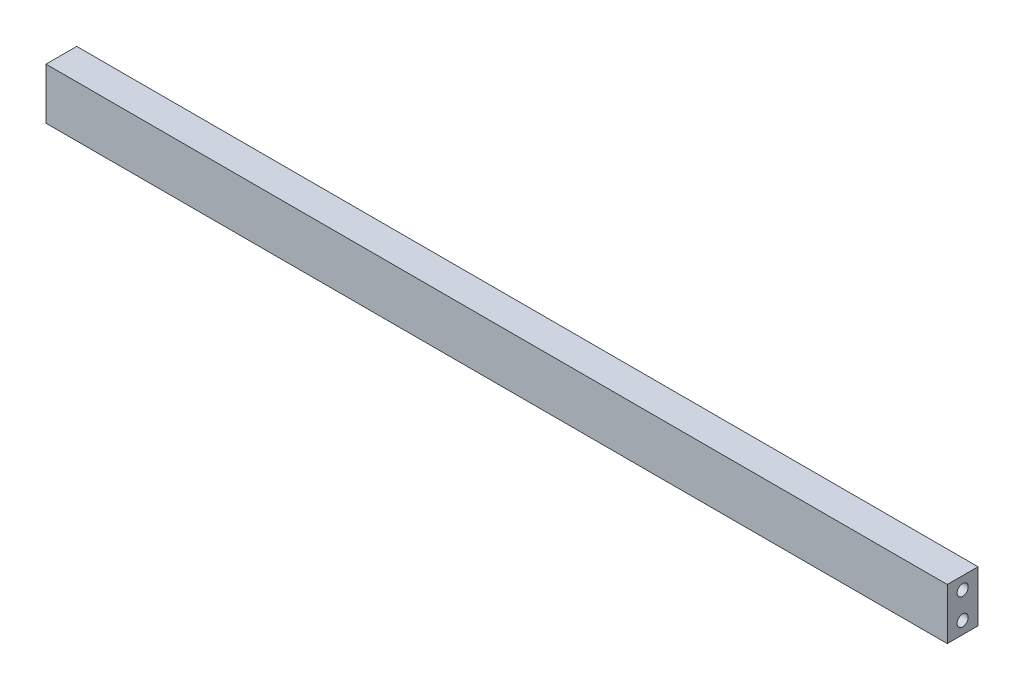
SolidWorks part; units mm, degrees
material "6061-T6 (SS)"
ref_plane "Front Plane" through (0, 0, 0) normal (0, 0, 1) x (1, 0, 0)
ref_plane "Top Plane" through (0, 0, 0) normal (0, 1, 0) x (1, 0, 0)
ref_plane "Right Plane" through (0, 0, 0) normal (1, 0, 0) x (0, 0, -1)
sketch "Sketch1" plane through (0, 0, 0) normal (1, 0, 0) x (0, 0, -1)
  line L1 (-4.7625, 7.9375) -> (4.7625, 7.9375)
  line L2 (-4.7625, 7.9375) -> (-4.7625, -7.9375)
  line L3 (-4.7625, -7.9375) -> (4.7625, -7.9375)
  line L4 (4.7625, 7.9375) -> (4.7625, -7.9375)
  line L5 (-4.7625, 7.9375) -> (4.7625, -7.9375) construction
  line L6 (-4.7625, -7.9375) -> (4.7625, 7.9375) construction
  point P0 (0, 0)
  dimension "D1" = 9.525
  dimension "D2" = 15.875
extrude "Boss-Extrude1" add sketch "Sketch1" along normal mid plane 279.4
sketch "Sketch2" plane through (139.7, 0, 0) normal (1, 0, 0) x (0, 0, -1)
  line L0 (0, 4.0894) -> (0, -4.0894) construction
  point P3 (0, 0)
  dimension "D1" = 8.1788
hole_wizard "Tap Drill for #8-32 Tap1" positions "Sketch3" profile "Sketch4" hole size "#8-32" standard "ANSI Inch"
sketch "Sketch3" plane through (139.7, 0, 0) normal (1, 0, 0) x (0, 0, -1)
  point P0 (0, 4.0894)
  point P3 (0, -4.0894)
sketch "Sketch4" plane through (139.7, 4.0894, 0) normal (0, 1, 0) x (0, 0, -1)
  line L0 (0, 0) -> (0, 11.1978)
  line L1 (0, 11.1978) -> (1.7272, 10.16)
  line L2 (1.7272, 10.16) -> (1.7272, 0)
  line L5 (1.7272, 0) -> (0, 0)
  line L10 (0, 11.1978) -> (-1.7272, 10.16) construction
  line L11 (0, -6.35) -> (0, 107.95) construction
  dimension "Hole Dia." = 3.4544
  dimension "Hole Depth" = 10.16
  dimension "Drill Angle" = 118
mirror "Mirror1" about plane through (0, 0, 0) normal (1, 0, 0) of "Tap Drill for #8-32 Tap1"
